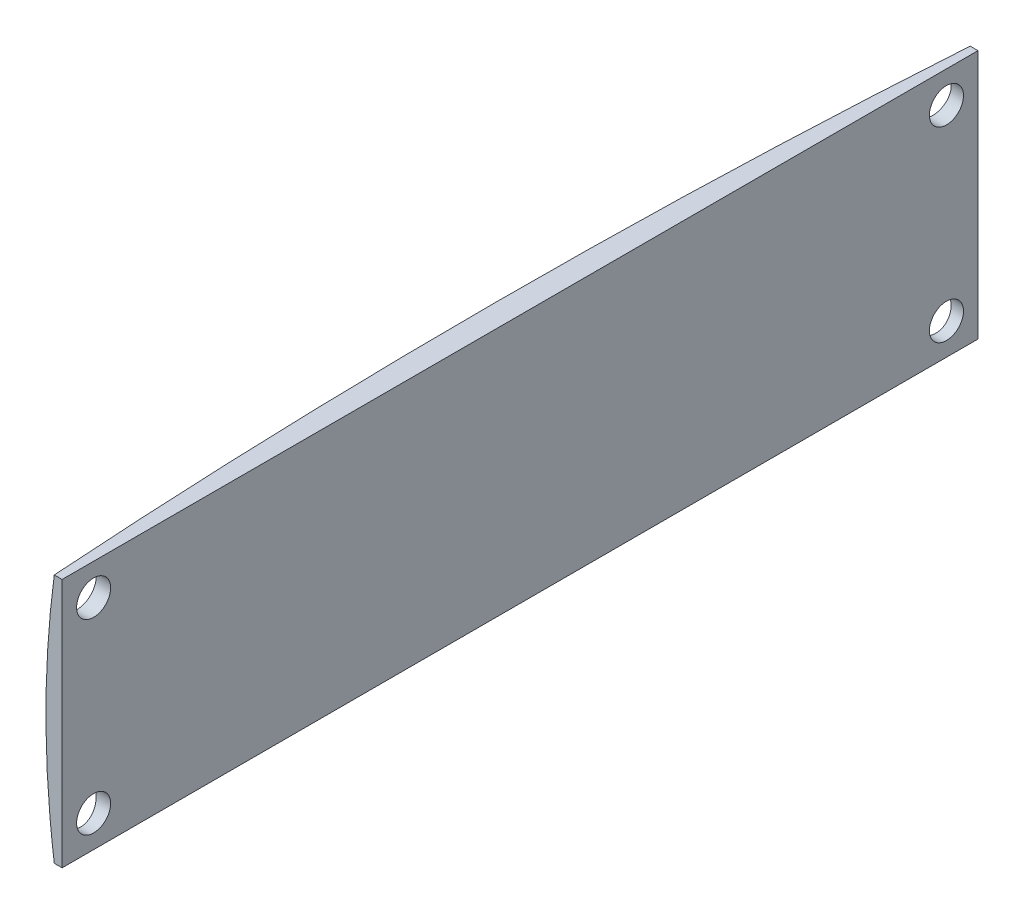
SolidWorks part; units mm, degrees
material "Nylon 101"
ref_plane "Front Plane" through (0, 0, 0) normal (0, 0, 1) x (1, 0, 0)
ref_plane "Top Plane" through (0, 0, 0) normal (0, 1, 0) x (1, 0, 0)
ref_plane "Right Plane" through (0, 0, 0) normal (1, 0, 0) x (0, 0, -1)
sketch "Sketch1" plane through (0, 0, 0) normal (0, 0, 1) x (1, 0, 0)
  line L0 (0, 0) -> (1372.87, 0) construction
  line L1 (1372.87, -509.27) -> (1372.87, 509.27)
  ellipse E0 centre (1372.87, 0) end of major axis (0, 0) minor radius 509.27 (1372.87, 509.27) -> (1372.87, -509.27) ccw
  point P4 (1372.87, 0)
  dimension "D1" = 1018.54
  dimension "D2" = 1372.87
revolve "Revolve1" add sketch "Sketch1" angle 360 about L1
sketch "Sketch2" plane through (0, 0, 0) normal (1, 0, 0) x (0, 0, -1)
  line L1 (92.202, 25.146) -> (-92.202, 25.146)
  line L2 (92.202, 25.146) -> (92.202, -25.146)
  line L3 (92.202, -25.146) -> (-92.202, -25.146)
  line L4 (-92.202, 25.146) -> (-92.202, -25.146)
  line L5 (92.202, 25.146) -> (-92.202, -25.146) construction
  line L6 (92.202, -25.146) -> (-92.202, 25.146) construction
  point P0 (0, 0)
  dimension "D1" = 184.404
  dimension "D2" = 50.292
extrude "Cut-Extrude2" cut sketch "Sketch2" against normal through all and the other way through all flip side to cut contours L1 L4 L3 L2
sketch "Sketch3" plane through (0, 0, 0) normal (1, 0, 0) x (0, 0, -1)
  line L1 (92.202, 25.146) -> (-92.202, 25.146)
  line L2 (92.202, 25.146) -> (92.202, -25.146)
  line L3 (92.202, -25.146) -> (-92.202, -25.146)
  line L4 (-92.202, 25.146) -> (-92.202, -25.146)
  line L5 (92.202, 25.146) -> (-92.202, -25.146) construction
  line L6 (92.202, -25.146) -> (-92.202, 25.146) construction
  point P0 (0, 0)
extrude "Cut-Extrude3" cut sketch "Sketch3" along normal through all from offset 6.35
sketch "Sketch4" plane through (6.35, 0, 0) normal (1, 0, 0) x (0, 0, -1)
  line L0 (92.202, 25.146) -> (-92.202, 25.146) construction
  line L1 (-92.202, 25.146) -> (-92.202, -25.146) construction
  line L2 (92.202, -25.146) -> (92.202, 25.146) construction
  line L3 (-92.202, -25.146) -> (92.202, -25.146) construction
  circle A0 centre (-85.852, 18.796) radius 3.429
  circle A1 centre (-85.852, -18.796) radius 3.429
  circle A2 centre (85.852, -18.796) radius 3.429
  circle A3 centre (85.852, 18.796) radius 3.429
  dimension "D1" = 6.35
  dimension "D5" = 6.858
  dimension "D2" = 6.35
  dimension "D3" = 6.35
  dimension "D4" = 6.35
extrude "Cut-Extrude4" cut sketch "Sketch4" against normal through all
